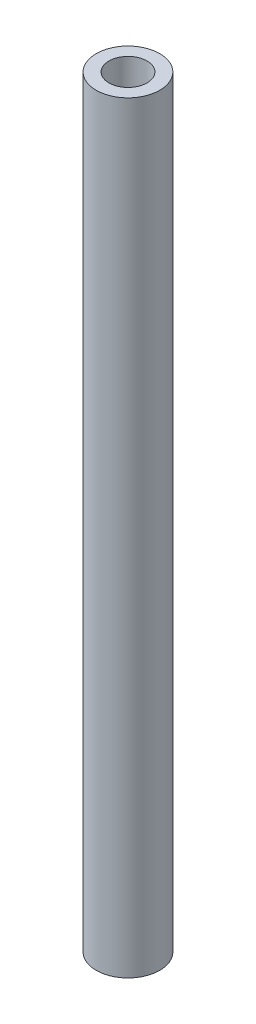
SolidWorks part; units mm, degrees
material "1060 合金"
ref_plane "前视基准面" through (0, 0, 0) normal (0, 0, 1) x (1, 0, 0)
ref_plane "上视基准面" through (0, 0, 0) normal (0, 1, 0) x (1, 0, 0)
ref_plane "右视基准面" through (0, 0, 0) normal (1, 0, 0) x (0, 0, -1)
other "Configuration Table"
sketch "草图1" plane through (0, 0, 0) normal (0, 1, 0) x (1, 0, 0)
  circle A0 centre (0, 0) radius 2.5
  circle A1 centre (0, 0) radius 1.5
  dimension "D1" = 3
  dimension "5" = 5
extrude "凸台-拉伸1" add sketch "草图1" along normal blind 60
